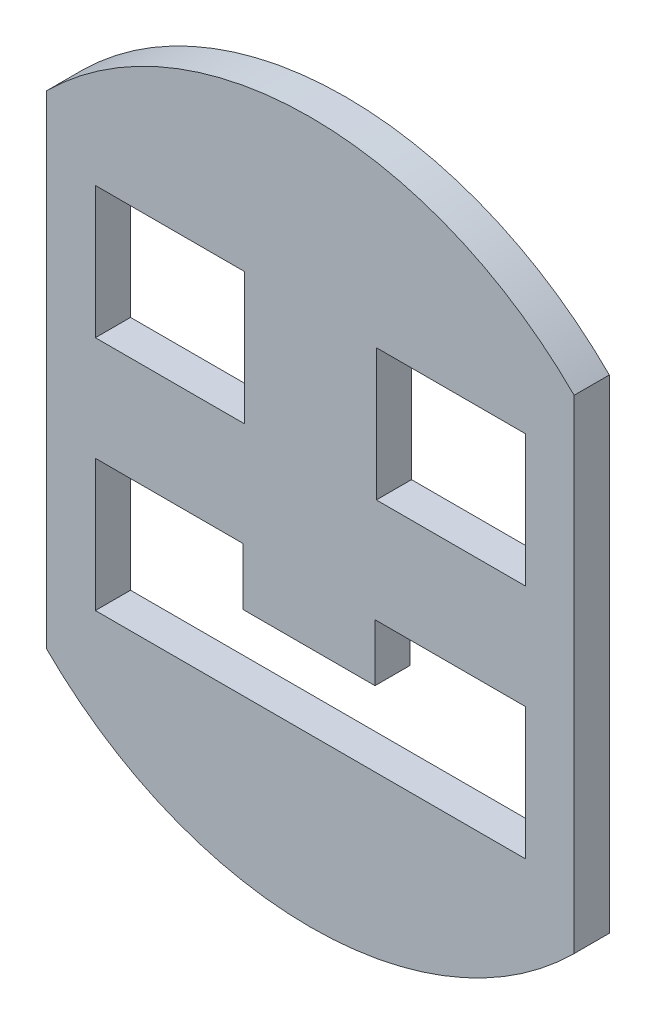
SolidWorks part; units mm, degrees
material "ABS"
ref_plane "Plano frontal" through (0, 0, 0) normal (0, 0, 1) x (1, 0, 0)
ref_plane "Plano superior" through (0, 0, 0) normal (0, 1, 0) x (1, 0, 0)
ref_plane "Plano direito" through (0, 0, 0) normal (1, 0, 0) x (0, 0, -1)
sketch "Esboço1" plane through (0, 0, 0) normal (0, 0, 1) x (1, 0, 0)
  line L0 (0, 0) -> (0, -110)
  line L1 (120, -110) -> (120, 0)
  line L2 (60, -12.6598) -> (60, -97.3402) construction
  line L3 (120, -55) -> (-37.4329, -55) construction
  line L8 (12.1875, -86.875) -> (107.8125, -23.125) construction
  line L9 (12.1875, -23.125) -> (107.8125, -86.875) construction
  arc A4 (0, 0) -> (120, 0) centre (60, -60.208) cw
  arc A5 (0, -110) -> (120, -110) centre (60, -49.792) ccw
  point P9 (60, -55)
  point P16 (0, 0)
  point P17 (60, 24.792)
  point P18 (0, 0)
  dimension "D1" = 110
  dimension "D5" = 85
  dimension "D2" = 63.75
  dimension "D3" = 95.625
extrude "Ressalto-extrusão1" add sketch "Esboço1" along normal blind 8
sketch "Esboço2" plane through (0, 0, 0) normal (0, 0, -1) x (-1, 0, 0)
  line L0 (-60, 24.792) -> (-60, -134.792) construction
  line L1 (-120, -55) -> (0, -55) construction
  line L2 (-120, -110) -> (-120, 0) construction
  line L3 (0, 0) -> (0, -110) construction
  line L4 (-108.9196, -96.875) -> (-11.0804, -96.875)
  line L5 (-108.9196, -43.125) -> (-75, -43.125)
  line L6 (-108.9196, -43.125) -> (-108.9196, -13.125)
  line L7 (-108.9196, -13.125) -> (-11.0804, -13.125)
  line L8 (-11.0804, -43.125) -> (-11.0804, -13.125)
  line L11 (-11.0804, -66.875) -> (-11.0804, -96.875)
  line L12 (-108.9196, -66.875) -> (-74.6956, -66.875)
  line L13 (-108.9196, -66.875) -> (-108.9196, -96.875)
  line L14 (-75, -43.125) -> (-75, -30.609)
  line L15 (-75, -30.609) -> (-45, -30.609)
  line L16 (-45, -30.609) -> (-45, -43.125)
  line L18 (-44.6956, -79.875) -> (-74.6956, -79.875)
  line L19 (-74.6956, -79.875) -> (-74.6956, -66.875)
  line L20 (-44.6956, -66.875) -> (-44.6956, -79.875)
  line L21 (-45, -43.125) -> (-11.0804, -43.125)
  line L22 (-44.6956, -66.875) -> (-11.0804, -66.875)
  arc A0 (0, 0) -> (-120, 0) centre (-60, -60.208) ccw construction
  arc A1 (-120, -110) -> (0, -110) centre (-60, -49.792) ccw construction
  point P14 (-60, -30.125)
  point P24 (-60, -79.875)
  point P26 (-60, -30.609)
  dimension "D1" = 30
  dimension "D2" = 83.75
  dimension "D3" = 30
  dimension "D4" = 30
  dimension "D6" = 97.8393
  dimension "D7" = 13
extrude "Corte-extrusão1" cut sketch "Esboço2" against normal blind 10 contours L6 L7 L8 L21 L16 L15 L14 L5 | L4 L11 L22 L20 L18 L19 L12 L13
sketch "Esboço3" plane through (0, -30.609, 0) normal (0, 1, 0) x (1, 0, 0)
  line L4 (75, -8) -> (75, 0)
  line L5 (75, 0) -> (45, 0)
  line L6 (45, 0) -> (45, -8)
  line L7 (45, -8) -> (75, -8)
  line L8 (75, -8) -> (75, 0)
  line L9 (75, 0) -> (45, 0)
  line L10 (45, 0) -> (45, -8)
  line L11 (45, -8) -> (75, -8)
  dimension "D1" = 0
extrude "Ressalto-extrusão2" add sketch "Esboço3" along normal up to next
sketch "Esboço4" plane through (0, 0, 0) normal (0, 0, -1) x (-1, 0, 0)
  circle A0 centre (-18.7084, -1.0648) radius 2.5
  circle A1 centre (-6.0938, -34.065) radius 2.5
  circle A2 centre (-6.0938, -75.94) radius 2.5
  circle A3 centre (-18.7084, -117.383) radius 2.5
  circle A4 centre (-60, -129.3825) radius 2.5
  circle A5 centre (-101.2916, -117.383) radius 2.5
  circle A6 centre (-113.9062, -75.94) radius 2.5
  circle A7 centre (-113.9062, -34.065) radius 2.5
  circle A8 centre (-101.2916, -1.0648) radius 2.5
  dimension "D1" = 5
extrude "Corte-extrusão2" cut sketch "Esboço4" against normal blind 3
